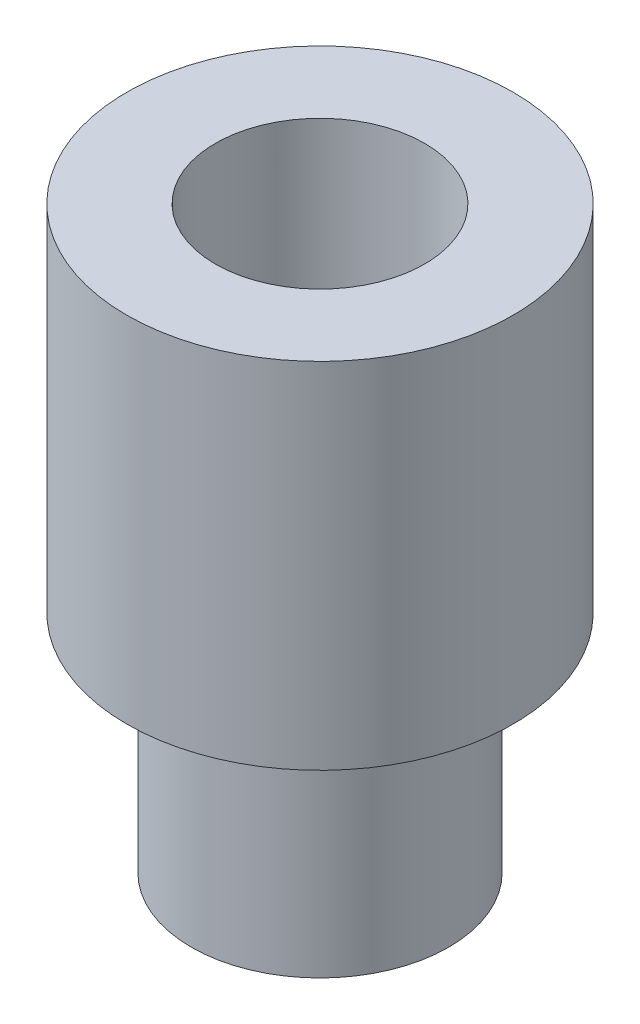
SolidWorks part; units mm, degrees
ref_plane "Alzado" through (0, 0, 0) normal (0, 0, 1) x (1, 0, 0)
ref_plane "Planta" through (0, 0, 0) normal (0, 1, 0) x (1, 0, 0)
ref_plane "Vista lateral" through (0, 0, 0) normal (1, 0, 0) x (0, 0, -1)
sketch "Croquis2" plane through (0, 0, 0) normal (0, 1, 0) x (1, 0, 0)
  circle A0 centre (0, 0) radius 3.25
  circle A1 centre (0, 0) radius 6
  dimension "D1" = 6.5
  dimension "D2" = 12
extrude "Saliente-Extruir1" add sketch "Croquis2" along normal blind 11
sketch "Croquis3" plane through (0, 0, 0) normal (0, -1, 0) x (1, 0, 0)
  circle A0 centre (0, 0) radius 4
  circle A1 centre (0, 0) radius 3.25 construction
  circle A2 centre (0, 0) radius 3.25
  dimension "D1" = 8
extrude "Saliente-Extruir2" add sketch "Croquis3" along normal blind 7
